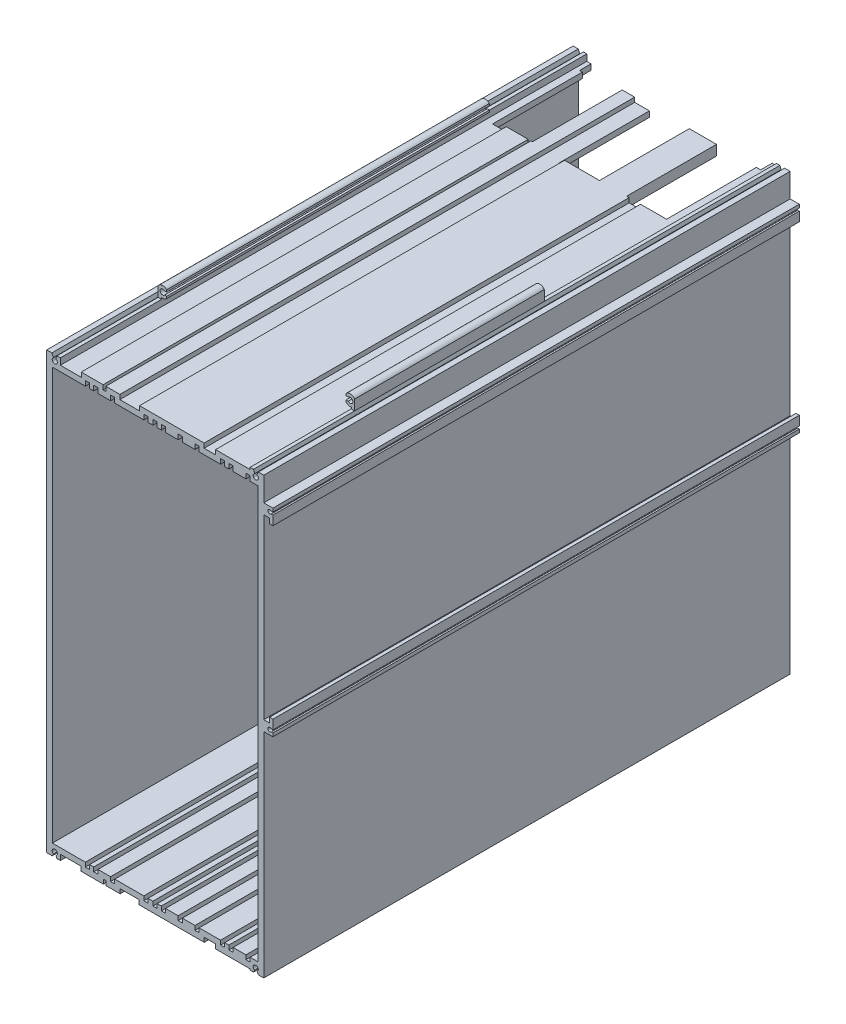
SolidWorks part; units mm, degrees
ref_plane "Front Plane" through (0, 0, 0) normal (0, 0, 1) x (1, 0, 0)
ref_plane "Top Plane" through (0, 0, 0) normal (0, 1, 0) x (1, 0, 0)
ref_plane "Right Plane" through (0, 0, 0) normal (1, 0, 0) x (0, 0, -1)
sketch "Sketch2" plane through (0, 0, 0) normal (0, 0, 1) x (1, 0, 0)
  line L0 (23.2732, 131.1707) -> (119.1108, 131.6725) construction
  line L1 (14.5, 261.3734) -> (14.5, 257.5858)
  line L2 (14.5, 257.5858) -> (26.7, 257.5858)
  line L3 (26.7, 257.5858) -> (26.7, 260.24)
  line L4 (26.7, 260.24) -> (39.5, 260.24)
  line L5 (39.5, 260.24) -> (39.5, 257.5858)
  line L6 (39.5, 257.5858) -> (41.1, 257.5858)
  line L7 (41.1, 257.5858) -> (41.1, 260.24)
  line L8 (41.1, 260.24) -> (49.3, 260.24)
  line L9 (49.3, 260.24) -> (49.3, 257.5858)
  line L10 (49.3, 257.5858) -> (60.8, 257.5858)
  line L11 (60.8, 257.5858) -> (60.8, 260.24)
  line L12 (60.8, 260.24) -> (98.6, 260.24)
  line L13 (98.6, 260.24) -> (98.6, 257.5858)
  line L14 (98.6, 257.5858) -> (105.3, 257.5858)
  line L15 (105.3, 257.5858) -> (105.3, 260.24)
  line L16 (105.3, 260.24) -> (125.5, 260.24)
  line L17 (125.5, 260.24) -> (125.5, 261.3734)
  line L18 (125.5, 261.3734) -> (127.5, 261.3734)
  line L19 (133.5, 261.3734) -> (133.5, 247.3734)
  line L20 (133.5, 247.3734) -> (138.85, 247.3734)
  line L21 (138.85, 247.3734) -> (138.85, 238.4234)
  line L22 (138.85, 238.4234) -> (136.9, 238.4234)
  line L23 (136.9, 238.4234) -> (136.9, 241.3734)
  line L24 (136.9, 241.3734) -> (133.5, 241.3734)
  line L25 (133.5, 241.3734) -> (133.5, 137.4734)
  line L26 (133.5, 137.4734) -> (136.9, 137.4734)
  line L27 (136.9, 137.4734) -> (136.9, 140.4234)
  line L28 (136.9, 140.4234) -> (138.85, 140.4234)
  line L29 (138.85, 140.4234) -> (138.85, 131.4734)
  line L30 (138.85, 131.4734) -> (133.5, 131.4734)
  line L31 (133.5, 131.4734) -> (133.5, 6.5734)
  line L32 (133.5, 6.5734) -> (130.3, 6.5734)
  line L33 (125.5, 6.5734) -> (125.5, 7.202)
  line L34 (125.5, 7.202) -> (105.25, 7.202)
  line L35 (105.25, 7.202) -> (105.25, 9.7858)
  line L36 (105.25, 9.7858) -> (98.65, 9.7858)
  line L37 (98.65, 9.7858) -> (98.65, 7.202)
  line L38 (98.65, 7.202) -> (60.55, 7.202)
  line L39 (60.55, 7.202) -> (60.55, 9.7858)
  line L40 (60.55, 9.7858) -> (49.45, 9.7858)
  line L41 (49.45, 9.7858) -> (49.45, 7.202)
  line L42 (49.45, 7.202) -> (41.2, 7.202)
  line L43 (41.2, 7.202) -> (41.2, 9.7858)
  line L44 (41.2, 9.7858) -> (39.6964, 9.7858)
  line L45 (39.6964, 9.7858) -> (39.6964, 7.202)
  line L46 (39.6964, 7.202) -> (26.5964, 7.202)
  line L47 (26.5964, 7.202) -> (26.5964, 9.7858)
  line L48 (26.5964, 9.7858) -> (14.4964, 9.7858)
  line L49 (14.4964, 9.7858) -> (14.4964, 6.5734)
  line L50 (14.4964, 6.5734) -> (12.4964, 6.5734)
  line L51 (6.5, 6.5734) -> (6.5, 261.3734)
  line L52 (6.5, 261.3734) -> (9.5, 261.3734)
  line L53 (9.8, 254.2858) -> (29.1, 254.2858)
  line L54 (29.1, 254.2858) -> (29.1, 257.1858)
  line L55 (29.1, 257.1858) -> (31.55, 257.1858)
  line L56 (31.55, 257.1858) -> (31.55, 254.2858)
  line L57 (31.55, 254.2858) -> (34, 254.2858)
  line L58 (34, 254.2858) -> (34, 257.1858)
  line L59 (34, 257.1858) -> (36.45, 257.1858)
  line L60 (36.45, 257.1858) -> (36.45, 254.2858)
  line L61 (36.45, 254.2858) -> (43.85, 254.2858)
  line L62 (43.85, 254.2858) -> (43.85, 257.1858)
  line L63 (43.85, 257.1858) -> (46.3, 257.1858)
  line L64 (46.3, 257.1858) -> (46.3, 254.2858)
  line L65 (46.3, 254.2858) -> (63.3, 254.2858)
  line L66 (63.3, 254.2858) -> (63.3, 257.1858)
  line L67 (63.3, 257.1858) -> (65.75, 257.1858)
  line L68 (65.75, 257.1858) -> (65.75, 254.2858)
  line L69 (65.75, 254.2858) -> (68.65, 254.2858)
  line L70 (68.65, 254.2858) -> (68.65, 257.1858)
  line L71 (68.65, 257.1858) -> (71.1, 257.1858)
  line L72 (71.1, 257.1858) -> (71.1, 254.2858)
  line L73 (71.1, 254.2858) -> (73.55, 254.2858)
  line L74 (73.55, 254.2858) -> (73.55, 257.1858)
  line L75 (73.55, 257.1858) -> (76, 257.1858)
  line L76 (76, 257.1858) -> (76, 254.2858)
  line L77 (76, 254.2858) -> (83.4, 254.2858)
  line L78 (83.4, 254.2858) -> (83.4, 257.1858)
  line L79 (83.4, 257.1858) -> (85.85, 257.1858)
  line L80 (85.85, 257.1858) -> (85.85, 254.2858)
  line L81 (85.85, 254.2858) -> (93.25, 254.2858)
  line L82 (93.25, 254.2858) -> (93.25, 257.1858)
  line L83 (93.25, 257.1858) -> (95.7, 257.1858)
  line L84 (95.7, 257.1858) -> (95.7, 254.2858)
  line L85 (95.7, 254.2858) -> (108.2, 254.2858)
  line L86 (108.2, 254.2858) -> (108.2, 257.1858)
  line L87 (108.2, 257.1858) -> (110.65, 257.1858)
  line L88 (110.65, 257.1858) -> (110.65, 254.2858)
  line L89 (110.65, 254.2858) -> (113.1, 254.2858)
  line L90 (113.1, 254.2858) -> (113.1, 257.1858)
  line L91 (113.1, 257.1858) -> (115.55, 257.1858)
  line L92 (115.55, 257.1858) -> (115.55, 254.2858)
  line L93 (115.55, 254.2858) -> (123.05, 254.2858)
  line L94 (123.05, 254.2858) -> (123.05, 257.1858)
  line L95 (123.05, 257.1858) -> (125.5, 257.1858)
  line L96 (125.5, 257.1858) -> (125.5, 254.2858)
  line L97 (125.5, 254.2858) -> (130.2, 254.2858)
  line L98 (130.2, 254.2858) -> (130.2, 13.0858)
  line L99 (130.2, 13.0858) -> (125.5, 13.0858)
  line L100 (125.5, 13.0858) -> (125.5, 10.6056)
  line L101 (125.5, 10.6056) -> (123.05, 10.6056)
  line L102 (123.05, 10.6056) -> (123.05, 13.0858)
  line L103 (123.05, 13.0858) -> (115.55, 13.0858)
  line L104 (115.55, 13.0858) -> (115.55, 10.6056)
  line L105 (115.55, 10.6056) -> (113.1, 10.6056)
  line L106 (113.1, 10.6056) -> (113.1, 13.0858)
  line L107 (113.1, 13.0858) -> (110.65, 13.0858)
  line L108 (110.65, 13.0858) -> (110.65, 10.6056)
  line L109 (110.65, 10.6056) -> (108.2, 10.6056)
  line L110 (108.2, 10.6056) -> (108.2, 13.0858)
  line L111 (108.2, 13.0858) -> (95.7, 13.0858)
  line L112 (95.7, 13.0858) -> (95.7, 10.6056)
  line L113 (95.7, 10.6056) -> (93.25, 10.6056)
  line L114 (93.25, 10.6056) -> (93.25, 13.0858)
  line L115 (93.25, 13.0858) -> (85.85, 13.0858)
  line L116 (85.85, 13.0858) -> (85.85, 10.6056)
  line L117 (85.85, 10.6056) -> (83.4, 10.6056)
  line L118 (83.4, 10.6056) -> (83.4, 13.0858)
  line L119 (83.4, 13.0858) -> (76, 13.0858)
  line L120 (76, 13.0858) -> (76, 10.6056)
  line L121 (76, 10.6056) -> (73.55, 10.6056)
  line L122 (73.55, 10.6056) -> (73.55, 13.0858)
  line L123 (73.55, 13.0858) -> (71.1, 13.0858)
  line L124 (71.1, 13.0858) -> (71.1, 10.6056)
  line L125 (71.1, 10.6056) -> (68.65, 10.6056)
  line L126 (68.65, 10.6056) -> (68.65, 13.0858)
  line L127 (68.65, 13.0858) -> (65.75, 13.0858)
  line L128 (65.75, 13.0858) -> (65.75, 10.6056)
  line L129 (65.75, 10.6056) -> (63.3, 10.6056)
  line L130 (63.3, 10.6056) -> (63.3, 13.0858)
  line L131 (63.3, 13.0858) -> (46.3, 13.0858)
  line L132 (46.3, 13.0858) -> (46.3, 10.6056)
  line L133 (46.3, 10.6056) -> (43.85, 10.6056)
  line L134 (43.85, 10.6056) -> (43.85, 13.0858)
  line L135 (43.85, 13.0858) -> (36.45, 13.0858)
  line L136 (36.45, 13.0858) -> (36.45, 10.6056)
  line L137 (36.45, 10.6056) -> (34, 10.6056)
  line L138 (34, 10.6056) -> (34, 13.0858)
  line L139 (34, 13.0858) -> (31.55, 13.0858)
  line L140 (31.55, 13.0858) -> (31.55, 10.6056)
  line L141 (31.55, 10.6056) -> (29.1, 10.6056)
  line L142 (29.1, 10.6056) -> (29.1, 13.0858)
  line L143 (29.1, 13.0858) -> (9.8, 13.0858)
  line L144 (9.8, 13.0858) -> (9.8, 254.2858)
  line L145 (11.2, 258.1858) -> (12.5, 261.3734)
  line L146 (11.2, 258.1858) -> (9.5, 261.3734)
  line L147 (12.5, 261.3734) -> (14.5, 261.3734)
  line L148 (128.8, 258.1858) -> (127.5, 261.3734)
  line L149 (128.8, 258.1858) -> (130.3, 261.3734)
  line L150 (130.3, 261.3734) -> (133.5, 261.3734)
  line L151 (138.85, 245.3734) -> (137.9352, 245.3734)
  line L152 (138.85, 243.8734) -> (137.8905, 243.8734)
  line L153 (138.85, 133.4734) -> (137.9352, 133.4734)
  line L154 (138.85, 134.9734) -> (137.8905, 134.9734)
  line L155 (128.8, 9.1858) -> (130.3, 6.5734)
  line L156 (128.8, 9.1858) -> (127.5, 6.5734)
  line L157 (127.5, 6.5734) -> (125.5, 6.5734)
  line L158 (11.2, 9.1858) -> (12.4964, 6.5734)
  line L159 (11.2, 9.1858) -> (9.7, 6.5734)
  line L160 (9.7, 6.5734) -> (6.5, 6.5734)
  circle A1 centre (11.2, 258.1858) radius 1.5
  circle A2 centre (128.8, 258.1858) radius 1.5
  circle A3 centre (137.075, 244.6484) radius 1.125
  circle A4 centre (137.075, 134.1984) radius 1.125
  circle A5 centre (128.8, 9.1858) radius 1.5
  circle A6 centre (11.2, 9.1858) radius 1.5
  point P51 (54.8, 13.0858)
  dimension "D1" = 127
  dimension "D87" = 3.2
  dimension "D90" = 3
  dimension "D92" = 2.4
  dimension "D93" = 3
  dimension "D97" = 5.75
  dimension "D101" = 5.75
  dimension "D106" = 3
  dimension "D111" = 3
  dimension "D2" = 3.3
  dimension "D3" = 3.3
  dimension "D4" = 120.4
  dimension "D5" = 8
  dimension "D6" = 8
  dimension "D7" = 3.3
  dimension "D8" = 3.3
  dimension "D9" = 254.8
  dimension "D10" = 247.8
  dimension "D11" = 241.2
  dimension "D12" = 12.2
  dimension "D13" = 12.8
  dimension "D14" = 1.6
  dimension "D15" = 37.8
  dimension "D16" = 8.2
  dimension "D17" = 11.5
  dimension "D18" = 6.7
  dimension "D19" = 20.2
  dimension "D20" = 19.3
  dimension "D21" = 2.9
  dimension "D22" = 2.45
  dimension "D23" = 2.45
  dimension "D24" = 2.45
  dimension "D25" = 2.45
  dimension "D26" = 2.45
  dimension "D27" = 2.45
  dimension "D28" = 2.45
  dimension "D29" = 2.45
  dimension "D30" = 2.45
  dimension "D31" = 2.45
  dimension "D32" = 2.45
  dimension "D33" = 2.45
  dimension "D34" = 7.4
  dimension "D35" = 17
  dimension "D36" = 19.3
  dimension "D37" = 2.9
  dimension "D38" = 2.45
  dimension "D39" = 7.4
  dimension "D40" = 7.4
  dimension "D41" = 12.5
  dimension "D42" = 2.45
  dimension "D43" = 7.5
  dimension "D44" = 4.7
  dimension "D45" = 2.45
  dimension "D46" = 2.45
  dimension "D47" = 2.45
  dimension "D48" = 7.4
  dimension "D49" = 2.45
  dimension "D50" = 17
  dimension "D51" = 2.45
  dimension "D52" = 2.9
  dimension "D53" = 2.45
  dimension "D54" = 2.45
  dimension "D55" = 2.45
  dimension "D56" = 7.4
  dimension "D57" = 2.45
  dimension "D58" = 7.4
  dimension "D59" = 2.45
  dimension "D60" = 12.5
  dimension "D61" = 2.45
  dimension "D62" = 2.45
  dimension "D63" = 2.45
  dimension "D64" = 7.5
  dimension "D65" = 2.45
  dimension "D66" = 4.7
  dimension "D67" = 7.9964
  dimension "D68" = 12.1
  dimension "D69" = 13.1
  dimension "D70" = 8.25
  dimension "D71" = 11.1
  dimension "D72" = 38.1
  dimension "D73" = 6.6
  dimension "D74" = 20.25
  dimension "D75" = 8
  dimension "D76" = 14
  dimension "D77" = 6
  dimension "D78" = 8.95
  dimension "D79" = 3.4
  dimension "D80" = 1.95
  dimension "D81" = 6
  dimension "D82" = 8.95
  dimension "D83" = 3.4
  dimension "D84" = 1.95
  dimension "D85" = 5.35
  dimension "D86" = 103.9
  dimension "D88" = 2.4
  dimension "D89" = 3
  dimension "D91" = 2
  dimension "D94" = 3.2
  dimension "D95" = 2
  dimension "D96" = 3.2
  dimension "D98" = 1.6
  dimension "D99" = 2
  dimension "D100" = 5.45
  dimension "D102" = 1.6
  dimension "D103" = 2
  dimension "D104" = 5.45
  dimension "D105" = 1.5
  dimension "D107" = 2.4
  dimension "D108" = 3.2
  dimension "D109" = 2
  dimension "D110" = 3.2
  dimension "D112" = 2.4
  dimension "D113" = 3.2
  dimension "D114" = 3.2
  dimension "D115" = 2
extrude "Boss-Extrude1" add sketch "Sketch2" along normal blind 308 contours A6 L158 L50 L49 L48 L47 L46 L45 L44 L43 L42 L41 L40 L39 L38 L37 L36 L35 L34 L33 L157 L156 A5 L155 L32 L31 L30 L29 L153 A4 L154 L28 L27 L26 L25 L24 L23 L22 L21 L152 A3 L151 L20 L19 L150 L149 A2 L148 L18
ref_plane "Plane1" through (0, 0, 60) normal (0, 0, -1) x (-1, 0, 0)
sketch "Sketch3" plane through (0, 0, 60) normal (0, 0, -1) x (-1, 0, 0)
  line L0 (-127.5, 261.3734) -> (-127.5, 267.3734)
  line L1 (-122.5, 270.1784) -> (-122.5, 262.1784)
  line L2 (-125.5, 261.3734) -> (-125.5, 269.0865)
  line L3 (-121.7757, 266.54) -> (-123.9222, 266.54)
  line L4 (-121.7757, 264.44) -> (-123.7503, 264.44)
  line L5 (-133.5, 251.3903) -> (-6.5, 251.3903) construction
  line L6 (-133.5, 261.3734) -> (-133.5, 247.3734) construction
  line L7 (-6.5, 6.5734) -> (-6.5, 261.3734) construction
  line L8 (-105.3, 260.24) -> (-125.5, 260.24) construction
  line L10 (-70, 251.3903) -> (-70, 270.1784) construction
  line L11 (-14.5, 261.3734) -> (-14.5, 269.0865)
  line L12 (-12.5, 261.3734) -> (-12.5, 267.3734)
  line L13 (-18.2243, 264.44) -> (-16.2497, 264.44)
  line L14 (-18.2243, 266.54) -> (-16.0778, 266.54)
  line L15 (-17.5, 270.1784) -> (-17.5, 262.1784)
  line L16 (-127.5, 261.3734) -> (-125.5, 261.3734)
  line L17 (-14.5, 261.3734) -> (-12.5, 261.3734)
  circle A0 centre (-124.8514, 265.49) radius 3.25
  circle A2 centre (-124.9004, 265.4028) radius 1.5
  circle A6 centre (-15.0996, 265.4028) radius 1.5
  circle A7 centre (-15.1486, 265.49) radius 3.25
  dimension "D1" = 6.5
  dimension "D5" = 3
  dimension "D6" = 1.85
  dimension "D2" = 5
  dimension "D3" = 6
  dimension "D4" = 2
  dimension "D7" = 2.2
  dimension "D8" = 2.2
extrude "Boss-Extrude2" add sketch "Sketch3" against normal blind 188.8 contours A7 L11 A6 L13 L15 | A7 L12 L11 A6 | L12 A7 L11 L17 | A7 L15 L14 A6 L11 | A0 L0 L16 L2 | A2 L2 A0 L0 | A2 L3 L1 A0 L2 | A2 L2 A0 L1 L4
sketch "Sketch4" plane through (127.5, 0, 0) normal (1, 0, 0) x (0, 0, -1)
  line L0 (-248.8, 261.3734) -> (-248.8, 267.3734) construction
  line L5 (-60, 261.3734) -> (-137.8, 261.3734)
  line L6 (-60, 261.3734) -> (-60, 282.1971)
  line L7 (-60, 282.1971) -> (-137.8, 282.1971)
  line L8 (-137.8, 261.3734) -> (-137.8, 282.1971)
  line L9 (-60, 261.3734) -> (-137.8, 282.1971) construction
  line L10 (-60, 282.1971) -> (-137.8, 261.3734) construction
  point P4 (-98.9, 271.7852)
  dimension "D1" = 111
extrude "Cut-Extrude3" cut sketch "Sketch4" against normal up to next
sketch "Sketch5" plane through (0, 260.24, 0) normal (0, 1, 0) x (1, 0, 0)
  line L0 (105.3, 0) -> (125.5, 0) construction
  line L1 (17, -6.75) -> (123, -6.75)
  line L2 (17, -6.75) -> (17, 0)
  line L3 (17, 0) -> (123, 0)
  line L4 (123, -6.75) -> (123, 0)
  line L5 (17, -6.75) -> (123, 0) construction
  line L6 (17, 0) -> (123, -6.75) construction
  line L7 (14.5, -60) -> (14.5, 0) construction
  line L8 (125.5, -137.8) -> (125.5, 0) construction
  point P4 (70, -3.375)
  dimension "D1" = 106
  dimension "D2" = 2.5
  dimension "D3" = 6.75
  dimension "D4" = 2.5
extrude "Cut-Extrude4" cut sketch "Sketch5" against normal up to next
sketch "Sketch6" plane through (0, 260.24, 0) normal (0, 1, 0) x (1, 0, 0)
  line L0 (105.3, -6.75) -> (123, -6.75) construction
  line L1 (120.5, -6.75) -> (97.15, -6.75)
  line L2 (120.5, -6.75) -> (120.5, -59.3)
  line L3 (120.5, -59.3) -> (97.15, -59.3)
  line L4 (97.15, -6.75) -> (97.15, -59.3)
  line L5 (120.5, -6.75) -> (97.15, -59.3) construction
  line L6 (120.5, -59.3) -> (97.15, -6.75) construction
  line L7 (125.5, -308) -> (125.5, 0) construction
  line L8 (133.5, 0) -> (138.85, 0) construction
  line L9 (60.8, -6.75) -> (98.6, -6.75) construction
  line L10 (81.25, -6.75) -> (57.9, -6.75)
  line L11 (81.25, -6.75) -> (81.25, -59.3)
  line L12 (81.25, -59.3) -> (57.9, -59.3)
  line L13 (57.9, -6.75) -> (57.9, -59.3)
  line L14 (81.25, -6.75) -> (57.9, -59.3) construction
  line L15 (81.25, -59.3) -> (57.9, -6.75) construction
  line L16 (60.8, -6.75) -> (49.3, -6.75) construction
  line L17 (42, -6.75) -> (18.65, -6.75)
  line L18 (42, -6.75) -> (42, -59.3)
  line L19 (42, -59.3) -> (18.65, -59.3)
  line L20 (18.65, -6.75) -> (18.65, -59.3)
  line L21 (42, -6.75) -> (18.65, -59.3) construction
  line L22 (42, -59.3) -> (18.65, -6.75) construction
  point P4 (108.825, -33.025)
  point P15 (69.575, -33.025)
  point P22 (30.325, -33.025)
  dimension "D1" = 23.35
  dimension "D2" = 5
  dimension "D3" = 52.55
  dimension "D4" = 59.3
  dimension "D5" = 52.55
  dimension "D6" = 15.9
  dimension "D7" = 23.35
  dimension "D8" = 23.35
  dimension "D9" = 15.9
extrude "Cut-Extrude5" cut sketch "Sketch6" against normal up to next
